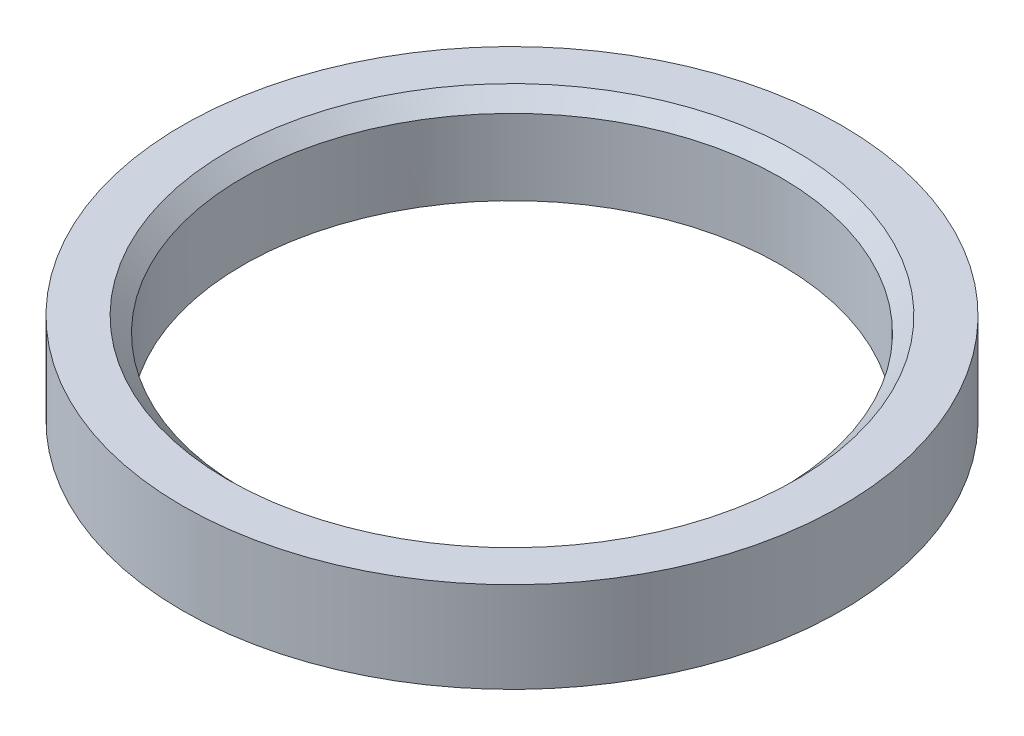
SolidWorks part; units mm, degrees
ref_plane "Plan de face" through (0, 0, 0) normal (0, 0, 1) x (1, 0, 0)
ref_plane "Plan de dessus" through (0, 0, 0) normal (0, 1, 0) x (1, 0, 0)
ref_plane "Plan de droite" through (0, 0, 0) normal (1, 0, 0) x (0, 0, -1)
sketch "Sketch1" plane through (0, 0, 0) normal (0, 0, 1) x (1, 0, 0)
  line L0 (0, 0) -> (0, 11.2472) construction
  line L2 (8.9, 0) -> (10.9, 0)
  line L3 (8.9, 0) -> (8.9, 3)
  line L4 (8.9, 3) -> (10.9, 3)
  line L5 (10.9, 0) -> (10.9, 3)
  dimension "D1" = 17.8
  dimension "D2" = 2
  dimension "D3" = 3
revolve "Revolve1" add sketch "Sketch1" angle 360 about L0
chamfer "Chamfer1" distance 0.5 angle 45 1 edges at (0, 3, -8.9)
